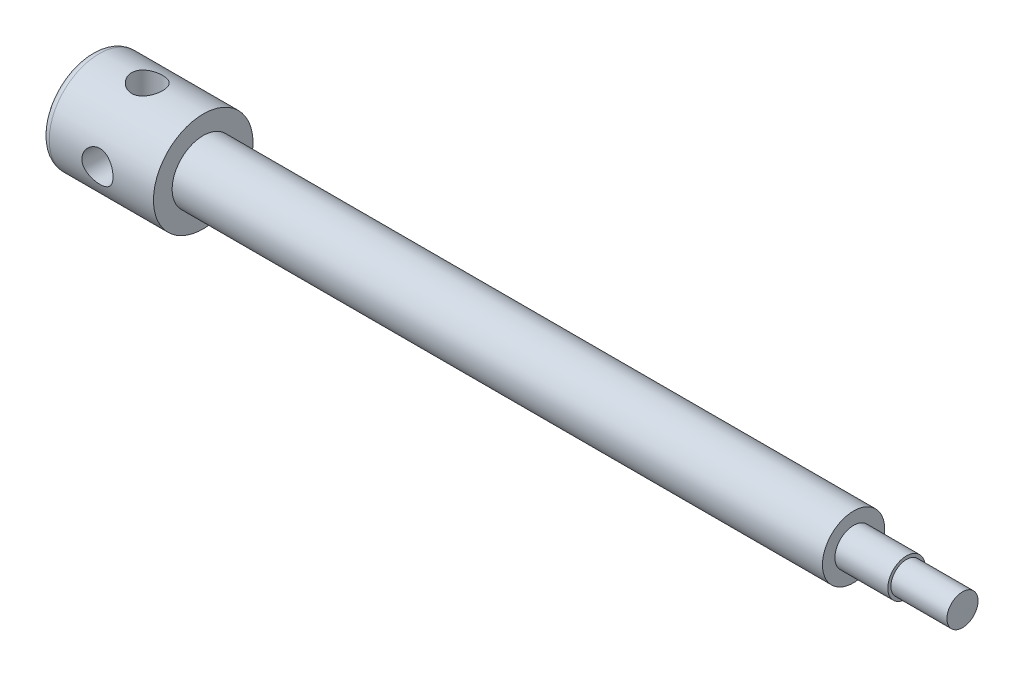
SolidWorks part; units mm, degrees
ref_plane "Front Plane" through (0, 0, 0) normal (0, 0, 1) x (1, 0, 0)
ref_plane "Top Plane" through (0, 0, 0) normal (0, 1, 0) x (1, 0, 0)
ref_plane "Right Plane" through (0, 0, 0) normal (1, 0, 0) x (0, 0, -1)
sketch "Sketch1" plane through (0, 0, 0) normal (0, 0, 1) x (1, 0, 0)
  line L0 (0, 0) -> (50000, 0) construction
  line L1 (-89.9262, 0) -> (-89.9262, 13.5)
  line L2 (-87.4262, 16) -> (-53.9262, 16)
  line L3 (-53.9262, 16) -> (-53.9262, 10)
  line L4 (-53.9262, 10) -> (155.0738, 10)
  line L5 (155.0738, 10) -> (155.0738, 6)
  line L6 (155.0738, 6) -> (172.0738, 6)
  line L7 (172.0738, 6) -> (172.0738, 5)
  line L8 (172.0738, 5) -> (190.0738, 5)
  line L9 (190.0738, 5) -> (190.0738, 0)
  line L10 (-89.9262, 0) -> (190.0738, 0)
  arc A0 (-89.9262, 13.5) -> (-87.4262, 16) centre (-87.4262, 13.5) cw
  point P15 (-89.9262, 16)
  dimension "D9" = 2.5
  dimension "D1" = 16
  dimension "D2" = 5
  dimension "D3" = 6
  dimension "D4" = 10
  dimension "D5" = 36
  dimension "D6" = 17
  dimension "D7" = 18
  dimension "D8" = 209
revolve "Revolve1" add sketch "Sketch1" angle 360 about L0
sketch "Sketch2" plane through (0, 0, 0) normal (0, 1, 0) x (1, 0, 0)
  line L0 (0, 0) -> (-120.5087, 0) construction
  line L1 (-71.9262, 16) -> (-71.9262, -9.2486) construction
  line L5 (-53.9262, 16) -> (-87.4262, 16) construction
  line L6 (-53.9262, -16) -> (-53.9262, 16) construction
  circle A0 centre (-71.9262, 0) radius 5
  dimension "D1" = 18
sketch "Sketch3" plane through (0, 0, 0) normal (0, 0, 1) x (1, 0, 0)
  line L0 (-100.1819, 0) -> (0, 0) construction
  line L1 (-53.9262, -16) -> (-53.9262, 16) construction
  circle A0 centre (-71.9262, 0) radius 5
  point P3 (-71.9262, 0)
  dimension "D2" = 10
  dimension "D1" = 18
extrude "Extrude2" cut sketch "Sketch3" against normal mid plane 40
extrude "Extrude3" cut sketch "Sketch2" against normal mid plane 40
